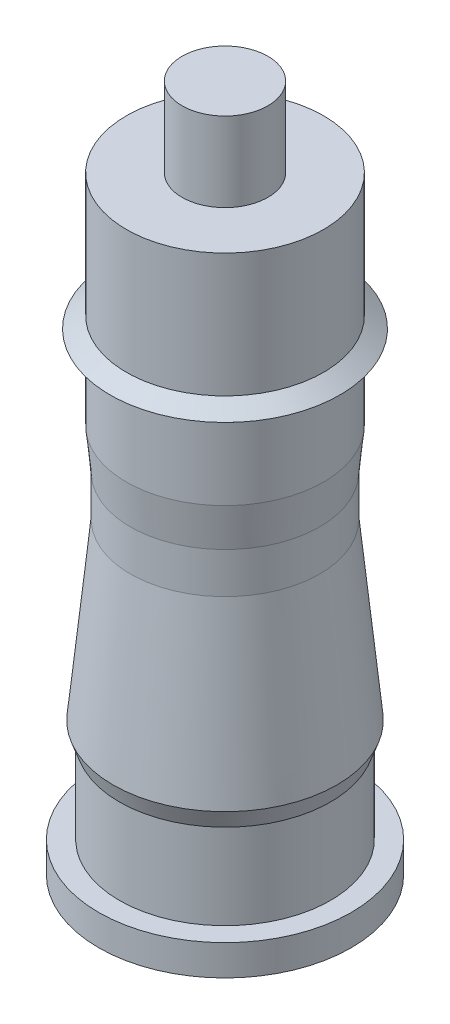
SolidWorks part; units mm, degrees
ref_plane "Front Plane" through (0, 0, 0) normal (0, 0, 1) x (1, 0, 0)
ref_plane "Top Plane" through (0, 0, 0) normal (0, 1, 0) x (1, 0, 0)
ref_plane "Right Plane" through (0, 0, 0) normal (1, 0, 0) x (0, 0, -1)
sketch "Sketch1" plane through (0, 0, 0) normal (0, 0, 1) x (1, 0, 0)
  line L0 (0, 0) -> (0, 58.0102) construction
  line L1 (0, 0) -> (6.9977, 0)
  line L2 (6.9977, 0) -> (6.9977, 0.7937)
  line L3 (6.9977, 0.7937) -> (8.7757, 0.7937)
  line L4 (8.7757, 0.7937) -> (8.7757, 0)
  line L5 (8.7757, 0) -> (9.8298, 0)
  line L6 (9.8298, 0) -> (9.8298, 2.3812)
  line L7 (9.8298, 2.3812) -> (8.2169, 2.3812)
  line L8 (8.2169, 2.3812) -> (8.2169, 9.017)
  line L9 (8.2169, 9.017) -> (8.7122, 10.414)
  line L10 (8.7122, 10.414) -> (7.366, 23.9522)
  line L11 (7.366, 23.9522) -> (7.366, 27.1272)
  line L12 (7.366, 27.1272) -> (7.6708, 30.3022)
  line L13 (7.6708, 30.3022) -> (7.6708, 35.9156)
  line L14 (7.6708, 35.9156) -> (8.9408, 36.8046)
  line L15 (8.9408, 36.8046) -> (7.6708, 37.6936)
  line L16 (7.6708, 37.6936) -> (7.6708, 47.3202)
  line L17 (7.6708, 47.3202) -> (3.3401, 47.3202)
  line L18 (3.3401, 47.3202) -> (3.3401, 53.4924)
  line L19 (3.3401, 53.4924) -> (0, 53.4924)
  line L20 (0, 53.4924) -> (0, 0)
  point P20 (7.8867, 0.7937)
  dimension "D1" = 53.4924
  dimension "D2" = 15.3416
  dimension "D3" = 6.6802
  dimension "D4" = 47.3202
  dimension "D5" = 14.732
  dimension "D6" = 16.4338
  dimension "D7" = 17.4244
  dimension "D8" = 19.6596
  dimension "D9" = 37.6936
  dimension "D10" = 23.9522
  dimension "D11" = 10.414
  dimension "D12" = 9.017
  dimension "D13" = 2.3813
  dimension "D14" = 3.175
  dimension "D15" = 3.175
  dimension "D16" = 1.778
  dimension "D17" = 17.8816
  dimension "D18" = 1.778
  dimension "D19" = 0.7937
  dimension "D20" = 15.7734
revolve "Revolve1" add sketch "Sketch1" angle 360 about L0
